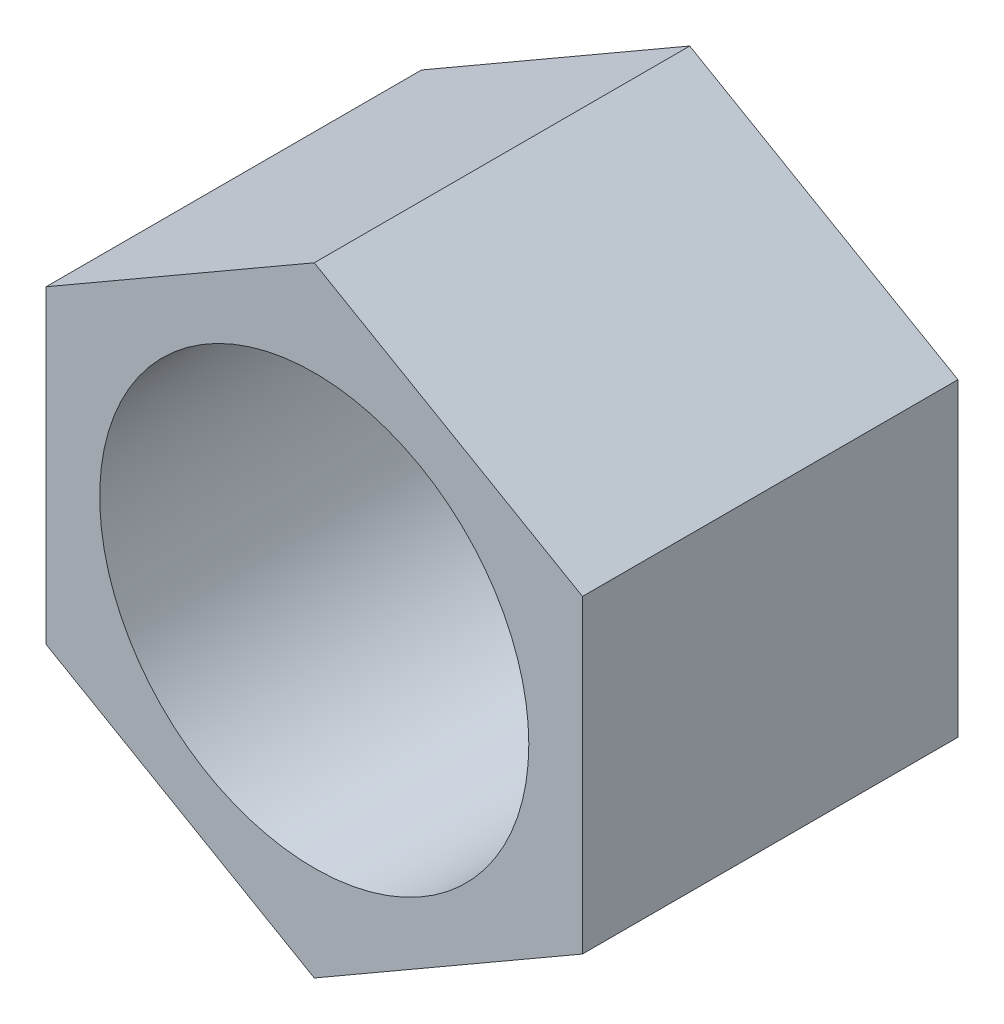
SolidWorks part; units mm, degrees
ref_plane "Front Plane" through (0, 0, 0) normal (0, 0, 1) x (1, 0, 0)
ref_plane "Top Plane" through (0, 0, 0) normal (0, 1, 0) x (1, 0, 0)
ref_plane "Right Plane" through (0, 0, 0) normal (1, 0, 0) x (0, 0, -1)
ref_plane "Plane1" through (0, 0, 13.5) normal (0, 0, 1) x (1, 0, 0)
sketch "Sketch1" plane through (0, 0, 13.5) normal (0, 0, 1) x (1, 0, 0)
  line L0 (-22.5, 18.5566) -> (-20, 17.1132)
  line L1 (-20, 17.1132) -> (-17.5, 18.5566)
  line L2 (-17.5, 18.5566) -> (-17.5, 21.4434)
  line L3 (-17.5, 21.4434) -> (-20, 22.8868)
  line L4 (-20, 22.8868) -> (-22.5, 21.4434)
  line L5 (-22.5, 21.4434) -> (-22.5, 18.5566)
  circle A0 centre (-20, 20) radius 2
extrude "Boss-Extrude1" add sketch "Sketch1" against normal blind 3.5
